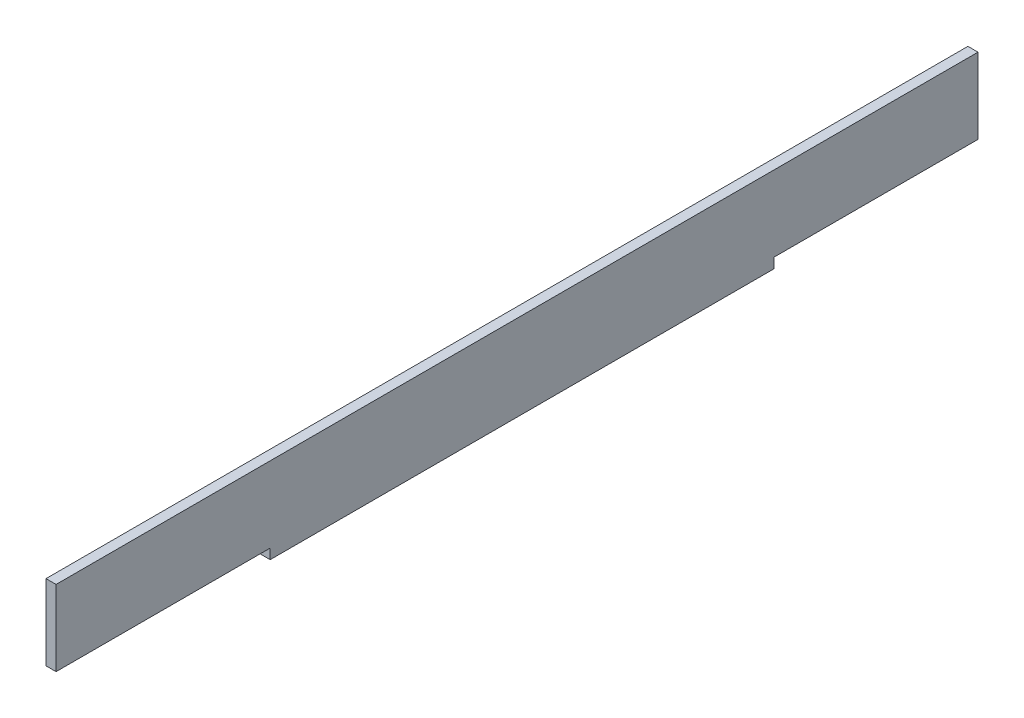
SolidWorks part; units mm, degrees
ref_plane "Front Plane" through (0, 0, 0) normal (0, 0, 1) x (1, 0, 0)
ref_plane "Top Plane" through (0, 0, 0) normal (0, 1, 0) x (1, 0, 0)
ref_plane "Right Plane" through (0, 0, 0) normal (1, 0, 0) x (0, 0, -1)
sketch "Sketch1" plane through (0, 0, 0) normal (1, 0, 0) x (0, 0, -1)
  line L0 (-97.2739, -16.9092) -> (102.7261, -16.9092)
  line L1 (102.7261, -16.9092) -> (102.7261, -12.9092)
  line L2 (102.7261, -12.9092) -> (183.7261, -12.9092)
  line L3 (183.7261, -12.9092) -> (183.7261, 17.0908)
  line L4 (183.7261, 17.0908) -> (102.7261, 17.0908)
  line L5 (102.7261, 17.0908) -> (-97.2739, 17.0908)
  line L6 (-97.2739, 17.0908) -> (-182.2739, 17.0908)
  line L7 (-182.2739, 17.0908) -> (-182.2739, -12.9092)
  line L8 (-182.2739, -12.9092) -> (-97.2739, -12.9092)
  line L9 (-97.2739, -12.9092) -> (-97.2739, -16.9092)
  dimension "D1" = 200
  dimension "D2" = 4
  dimension "D3" = 81
  dimension "D4" = 30
  dimension "D5" = 200
  dimension "D6" = 85
  dimension "D7" = 30
  dimension "D8" = 85
  dimension "D9" = 4
extrude "Boss-Extrude1" add sketch "Sketch1" along normal blind 4
